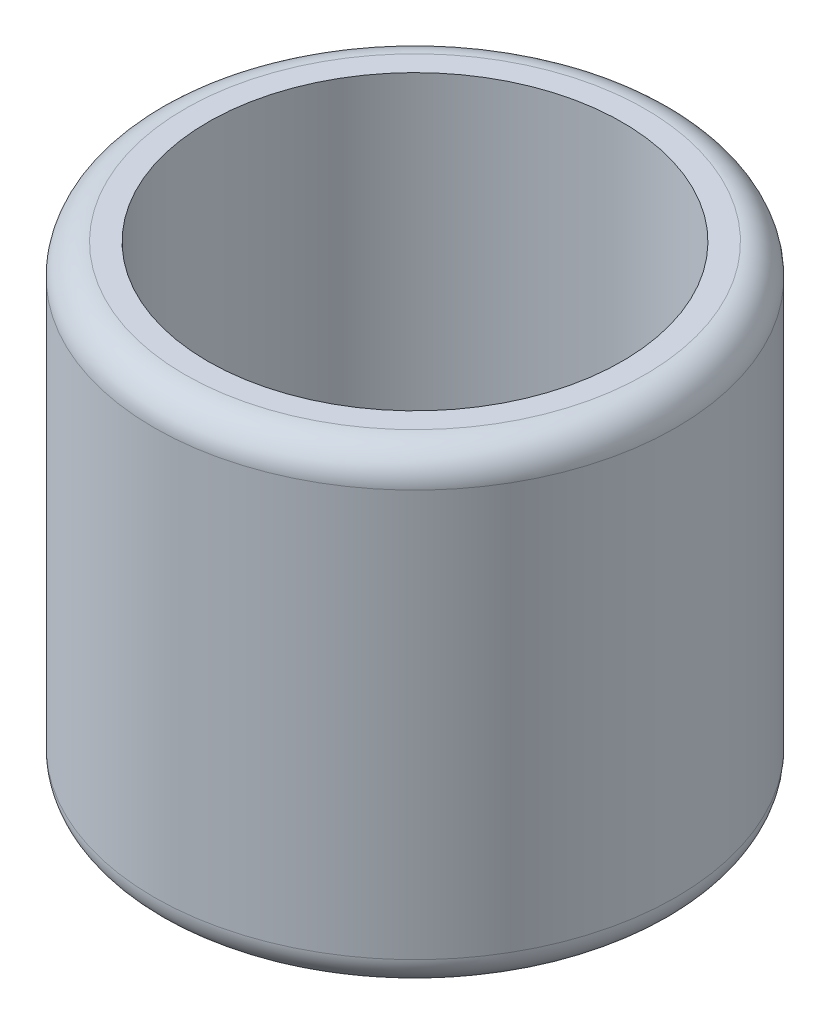
SolidWorks part; units mm, degrees
ref_plane "Front Plane" through (0, 0, 0) normal (0, 0, 1) x (1, 0, 0)
ref_plane "Top Plane" through (0, 0, 0) normal (0, 1, 0) x (1, 0, 0)
ref_plane "Right Plane" through (0, 0, 0) normal (1, 0, 0) x (0, 0, -1)
sketch "Sketch1" plane through (0, 0, 0) normal (0, 1, 0) x (1, 0, 0)
  circle A1 centre (0, 0) radius 17
extrude "Boss-Extrude1" add sketch "Sketch1" along normal blind 4 contours A1
sketch "Sketch2" plane through (0, 4, 0) normal (0, 1, 0) x (1, 0, 0)
  circle A0 centre (0, 0) radius 17
  circle A1 centre (0, 0) radius 13.5
extrude "Boss-Extrude2" add sketch "Sketch2" along normal blind 26.5 contours A0 | A1
fillet "Fillet1" radius 2 2 edges at (0, 30.5, 17) (0, 0, 17)
